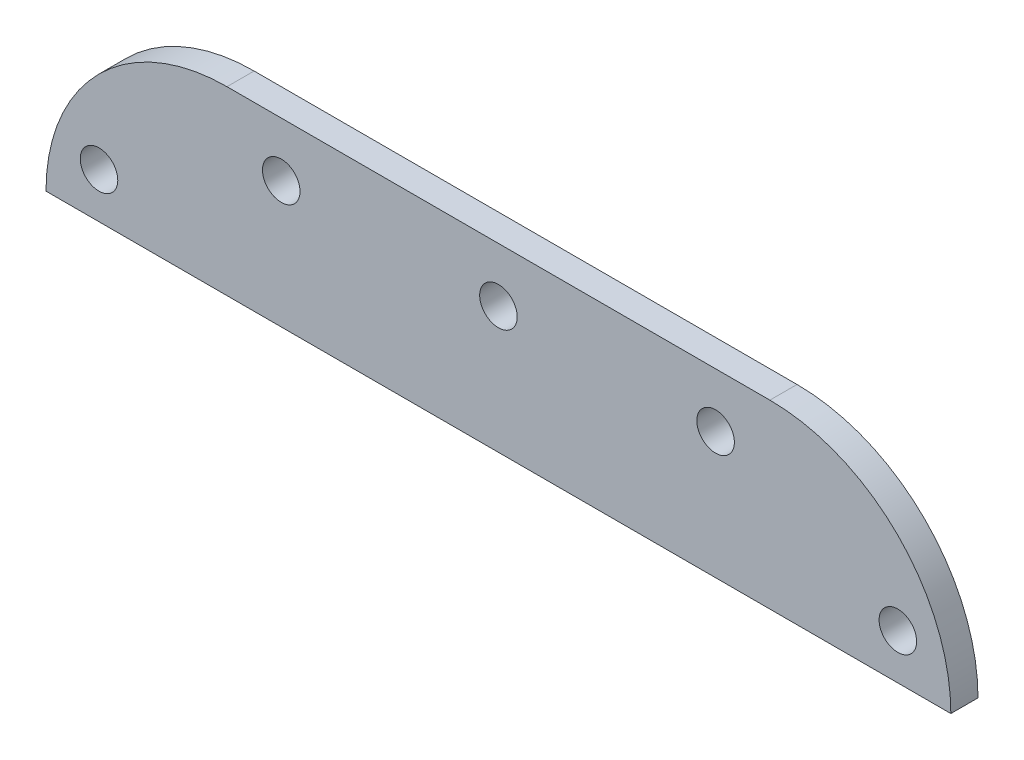
SolidWorks part; units mm, degrees
ref_plane "Front Plane" through (0, 0, 0) normal (0, 0, 1) x (1, 0, 0)
ref_plane "Top Plane" through (0, 0, 0) normal (0, 1, 0) x (1, 0, 0)
ref_plane "Right Plane" through (0, 0, 0) normal (1, 0, 0) x (0, 0, -1)
sketch "Sketch1" plane through (0, 0, 0) normal (0, 0, 1) x (1, 0, 0)
  line L0 (-48, 8) -> (0, 8) construction
  line L1 (-60, 20) -> (60, 20)
  line L3 (-100, -20) -> (100, -20)
  line L5 (-100, 20) -> (100, -20) construction
  line L6 (-100, -20) -> (100, 20) construction
  line L7 (0, 8) -> (48, 8) construction
  line L8 (0, 37.7846) -> (0, -45.3301) construction
  line L9 (-110.8398, 0) -> (122.7505, 0) construction
  circle A0 centre (0, 8) radius 4.15
  circle A1 centre (48, 8) radius 4.15
  circle A2 centre (-48, 8) radius 4.15
  circle A3 centre (-88.2843, -10) radius 4.15
  circle A4 centre (88.2843, -10) radius 4.15
  circle A5 centre (-48, 8) radius 19 construction
  arc A7 (-60, 20) -> (-100, -20) centre (-60, -20) ccw
  arc A8 (60, 20) -> (100, -20) centre (60, -20) cw
  circle A9 centre (-88.2843, -10) radius 10 construction
  circle A10 centre (88.2843, -10) radius 10 construction
  point P0 (0, 0)
  point P25 (0, 20)
  point P26 (0, -20)
  dimension "D4" = 8.3
  dimension "D6" = 38
  dimension "D1" = 40
  dimension "D2" = 200
  dimension "D3" = 12
  dimension "D5" = 48
  dimension "D7" = 40
  dimension "D8" = 200
extrude "Boss-Extrude1" add sketch "Sketch1" along normal blind 6
